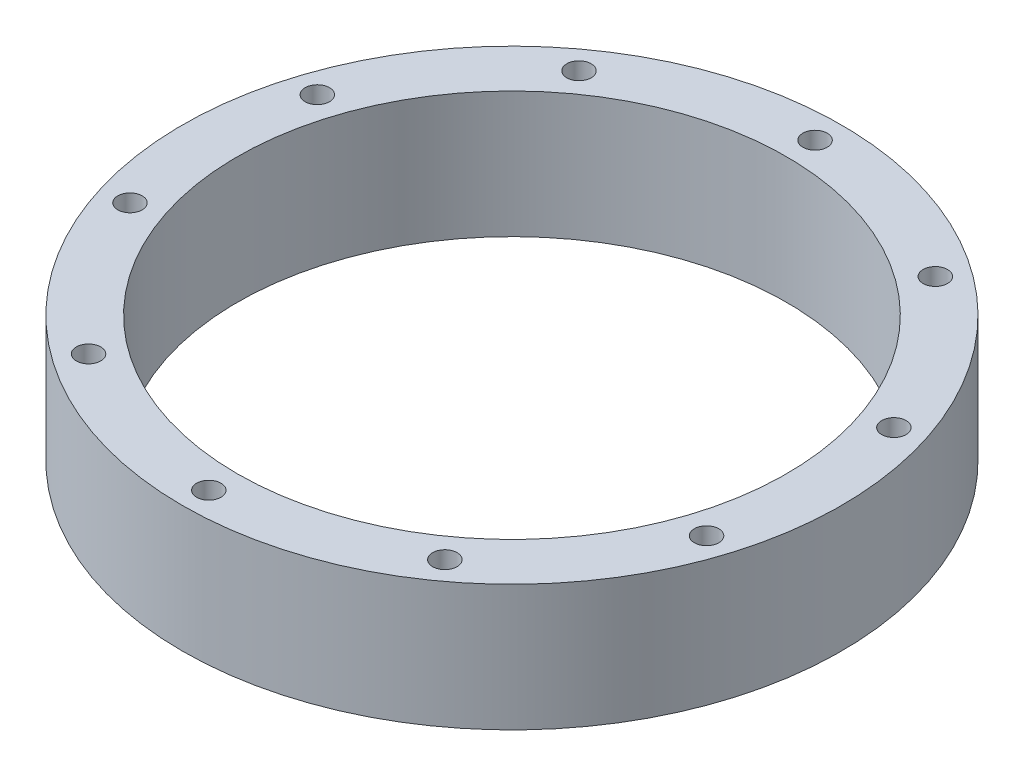
SolidWorks part; units mm, degrees
ref_plane "Front Plane" through (0, 0, 0) normal (0, 0, 1) x (1, 0, 0)
ref_plane "Top Plane" through (0, 0, 0) normal (0, 1, 0) x (1, 0, 0)
ref_plane "Right Plane" through (0, 0, 0) normal (1, 0, 0) x (0, 0, -1)
sketch "Sketch1" plane through (0, 0, 0) normal (0, 1, 0) x (1, 0, 0)
  circle A0 centre (0, 0) radius 40.5
  circle A1 centre (0, 0) radius 37.25 construction
  circle A2 centre (0, 37.25) radius 1.5
  circle A3 centre (21.895, 30.1359) radius 1.5
  circle A4 centre (35.4269, 11.5109) radius 1.5
  circle A5 centre (35.4269, -11.5109) radius 1.5
  circle A6 centre (21.895, -30.1359) radius 1.5
  circle A7 centre (0, -37.25) radius 1.5
  circle A8 centre (-21.895, -30.1359) radius 1.5
  circle A9 centre (-35.4269, -11.5109) radius 1.5
  circle A10 centre (-35.4269, 11.5109) radius 1.5
  circle A11 centre (-21.895, 30.1359) radius 1.5
  circle A12 centre (0, 0) radius 33.75
  point P26 (0, 0)
  dimension "D1" = 81
  dimension "D2" = 74.5
  dimension "D3" = 3
  dimension "D5" = 67.5
  dimension "D4" = 10
extrude "Boss-Extrude1" add sketch "Sketch1" along normal blind 15.5
